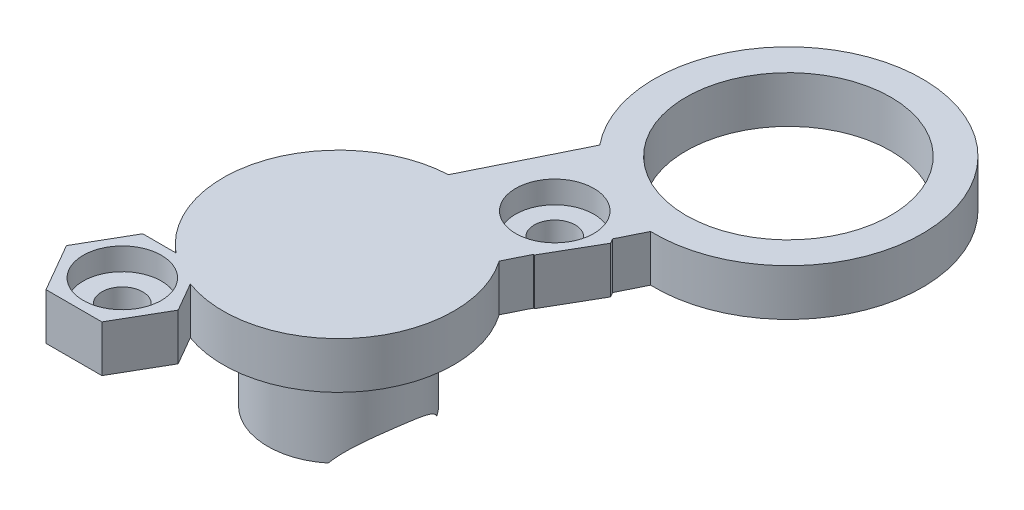
SolidWorks part; units mm, degrees
other "Compression Link 1 Moving Ball Retainer"
other "Compression Link 1 Moving Ball Retainer Left"
ref_plane "Front Plane" through (0, 0, 0) normal (0, 0, 1) x (1, 0, 0)
ref_plane "Top Plane" through (0, 0, 0) normal (0, 1, 0) x (1, 0, 0)
ref_plane "Right Plane" through (0, 0, 0) normal (1, 0, 0) x (0, 0, -1)
sketch3d "Retainer Feature 1 profile datum points"
  point P0 (-82.2724, -101, -15)
  point P1 (-72.2724, -101, -15)
  point P2 (-82.2724, -101, -5)
ref_plane "Retainer Feature 1 profile plane" through (0, -101, 0) normal (0, -1, 0) x (-1, 0, 0)
sketch "Retainer Feature 1 profile" plane through (0, -101, 0) normal (0, -1, 0) x (-1, 0, 0)
  circle A0 centre (82.2724, 15) radius 3.8
extrude "Retainer Feature 1" add sketch "Retainer Feature 1 profile" along normal blind 5.02 separate body
sketch3d "Retainer Feature 2 profile datum points"
  point P0 (-82.2724, -106, -15)
  point P1 (-72.2724, -106, -15)
  point P2 (-82.2724, -106, -5)
ref_plane "Retainer Feature 2 profile plane" through (0, -106, 0) normal (0, -1, 0) x (-1, 0, 0)
sketch "Retainer Feature 2 profile" plane through (0, -106, 0) normal (0, -1, 0) x (-1, 0, 0)
  circle A0 centre (82.2724, 15) radius 6.2
extrude "Retainer Feature 2" add sketch "Retainer Feature 2 profile" along normal blind 2.5
sketch3d "Middle Right Floating Compression Ball Retainer 1 Hexagonal Screw Pad 2 datum points"
  point P0 (-86.5224, -106, -7.6388)
  point P1 (-76.5224, -106, -7.6388)
  point P2 (-86.5224, -106, 2.3612)
ref_plane "Middle Right Floating Compression Ball Retainer 1 Hexagonal Screw Pad 2 plane" through (0, -106, 0) normal (0, -1, 0) x (-1, 0, 0)
sketch "Middle Right Floating Compression Ball Retainer 1 Hexagonal Screw Pad 2" plane through (0, -106, 0) normal (0, -1, 0) x (-1, 0, 0)
  line L0 (83.5224, 7.6388) -> (85.0224, 5.0407)
  line L1 (85.0224, 5.0407) -> (88.0224, 5.0407)
  line L2 (88.0224, 5.0407) -> (89.5224, 7.6388)
  line L3 (89.5224, 7.6388) -> (88.0224, 10.2369)
  line L4 (88.0224, 10.2369) -> (85.0224, 10.2369)
  line L5 (85.0224, 10.2369) -> (83.5224, 7.6388)
extrude "Retainer Feature 5" add sketch "Middle Right Floating Compression Ball Retainer 1 Hexagonal Screw Pad 2" along normal blind 2.5
sketch3d "Middle Right Floating Compression Ball Retainer 1 Hexagonal Screw Pad 5 datum points"
  point P0 (-78.0224, -106, -22.3612)
  point P1 (-68.0224, -106, -22.3612)
  point P2 (-78.0224, -106, -12.3612)
ref_plane "Middle Right Floating Compression Ball Retainer 1 Hexagonal Screw Pad 5 plane" through (0, -106, 0) normal (0, -1, 0) x (-1, 0, 0)
sketch "Middle Right Floating Compression Ball Retainer 1 Hexagonal Screw Pad 5" plane through (0, -106, 0) normal (0, -1, 0) x (-1, 0, 0)
  line L0 (75.0224, 22.3612) -> (76.5224, 19.7631)
  line L1 (76.5224, 19.7631) -> (79.5224, 19.7631)
  line L2 (79.5224, 19.7631) -> (81.0224, 22.3612)
  line L3 (81.0224, 22.3612) -> (79.5224, 24.9593)
  line L4 (79.5224, 24.9593) -> (76.5224, 24.9593)
  line L5 (76.5224, 24.9593) -> (75.0224, 22.3612)
extrude "Retainer Feature 8" add sketch "Middle Right Floating Compression Ball Retainer 1 Hexagonal Screw Pad 5" along normal blind 2.5
sketch3d "Retainer Feature 9 axis line"
  line L0 (-82.2724, -101, -25) -> (-82.2724, -101, -5) construction
ref_axis "Retainer Feature 9 axis" through (-82.2724, -101, -25) along (0, 0, 1)
sketch3d "Retainer Feature 9 profile datum points"
  point P0 (-82.2724, -101, -15)
  point P1 (-72.2724, -101, -15)
  point P2 (-82.2724, -101, -5)
ref_plane "Retainer Feature 9 profile plane" through (0, -101, 0) normal (0, -1, 0) x (-1, 0, 0)
sketch "Retainer Feature 9 profile" plane through (0, -101, 0) normal (0, -1, 0) x (-1, 0, 0)
  line L0 (82.2724, 11.85) -> (82.2724, 18.15)
  arc A0 (82.2724, 18.15) -> (82.2724, 11.85) centre (82.2724, 15) ccw
revolve "Retainer Feature 9" cut sketch "Retainer Feature 9 profile" angle 360 about axis through (-82.2724, -101, -25) along (0, 0, 1)
sketch3d "Middle Right Floating Compression Ball Retainer 1 Plate Sketch 49 datum points"
  point P0 (-82.2724, -106, -15)
  point P1 (-77.8481, -106, -23.968)
  point P2 (-73.3044, -106, -10.5757)
ref_plane "Middle Right Floating Compression Ball Retainer 1 Plate Sketch 49 plane" through (0, -106, 0) normal (0, -1, 0) x (-1, 0, 0)
sketch "Middle Right Floating Compression Ball Retainer 1 Plate Sketch 49" plane through (0, -106, 0) normal (0, -1, 0) x (-1, 0, 0)
  line L0 (84.9628, 16.3273) -> (76.9821, 32.5042)
  line L1 (76.9821, 32.5042) -> (71.6012, 29.8496)
  line L2 (71.6012, 29.8496) -> (79.582, 13.6727)
  line L3 (79.582, 13.6727) -> (84.9628, 16.3273)
extrude "Retainer Feature 12" add sketch "Middle Right Floating Compression Ball Retainer 1 Plate Sketch 49" along normal blind 2.5
sketch3d "Retainer Feature 13 profile datum points"
  point P0 (-74.2917, -106, -31.1769)
  point P1 (-64.2917, -106, -31.1769)
  point P2 (-74.2917, -106, -21.1769)
ref_plane "Retainer Feature 13 profile plane" through (0, -106, 0) normal (0, -1, 0) x (-1, 0, 0)
sketch "Retainer Feature 13 profile" plane through (0, -106, 0) normal (0, -1, 0) x (-1, 0, 0)
  circle A0 centre (74.2917, 31.1769) radius 7.2
extrude "Retainer Feature 13" add sketch "Retainer Feature 13 profile" along normal blind 2.5
sketch3d "Retainer Feature 14 profile datum points"
  point P0 (-74.2917, -105.9, -31.1769)
  point P1 (-64.2917, -105.9, -31.1769)
  point P2 (-74.2917, -105.9, -21.1769)
ref_plane "Retainer Feature 14 profile plane" through (0, -105.9, 0) normal (0, -1, 0) x (-1, 0, 0)
sketch "Retainer Feature 14 profile" plane through (0, -105.9, 0) normal (0, -1, 0) x (-1, 0, 0)
  circle A0 centre (74.2917, 31.1769) radius 5.5
extrude "Retainer Feature 14" cut sketch "Retainer Feature 14 profile" along normal blind 2.7
sketch3d "Retainer Feature 15 profile datum points"
  point P0 (-86.5224, -105, -7.6388)
  point P1 (-76.5224, -105, -7.6388)
  point P2 (-86.5224, -105, 2.3612)
ref_plane "Retainer Feature 15 profile plane" through (0, -105, 0) normal (0, -1, 0) x (-1, 0, 0)
sketch "Retainer Feature 15 profile" plane through (0, -105, 0) normal (0, -1, 0) x (-1, 0, 0)
  circle A0 centre (86.5224, 7.6388) radius 1.1
extrude "Retainer Feature 15" cut sketch "Retainer Feature 15 profile" along normal blind 3.75
sketch3d "Retainer Feature 16 profile datum points"
  point P0 (-86.5224, -107.3, -7.6388)
  point P1 (-76.5224, -107.3, -7.6388)
  point P2 (-86.5224, -107.3, 2.3612)
ref_plane "Retainer Feature 16 profile plane" through (0, -107.3, 0) normal (0, -1, 0) x (-1, 0, 0)
sketch "Retainer Feature 16 profile" plane through (0, -107.3, 0) normal (0, -1, 0) x (-1, 0, 0)
  circle A0 centre (86.5224, 7.6388) radius 2.1
extrude "Retainer Feature 16" cut sketch "Retainer Feature 16 profile" along normal blind 1.45
sketch3d "Retainer Feature 17 profile datum points"
  point P0 (-78.0224, -105, -22.3612)
  point P1 (-68.0224, -105, -22.3612)
  point P2 (-78.0224, -105, -12.3612)
ref_plane "Retainer Feature 17 profile plane" through (0, -105, 0) normal (0, -1, 0) x (-1, 0, 0)
sketch "Retainer Feature 17 profile" plane through (0, -105, 0) normal (0, -1, 0) x (-1, 0, 0)
  circle A0 centre (78.0224, 22.3612) radius 1.1
extrude "Retainer Feature 17" cut sketch "Retainer Feature 17 profile" along normal blind 3.75
sketch3d "Retainer Feature 18 profile datum points"
  point P0 (-78.0224, -107.3, -22.3612)
  point P1 (-68.0224, -107.3, -22.3612)
  point P2 (-78.0224, -107.3, -12.3612)
ref_plane "Retainer Feature 18 profile plane" through (0, -107.3, 0) normal (0, -1, 0) x (-1, 0, 0)
sketch "Retainer Feature 18 profile" plane through (0, -107.3, 0) normal (0, -1, 0) x (-1, 0, 0)
  circle A0 centre (78.0224, 22.3612) radius 2.1
extrude "Retainer Feature 18" cut sketch "Retainer Feature 18 profile" along normal blind 1.45
sketch3d "Articulation Throat axis line"
  line L0 (-90.6158, -106.3831, -16.1872) -> (-73.929, -95.6169, -13.8128) construction
ref_axis "Articulation Throat axis" through (-90.6158, -106.3831, -16.1872) along (0.8343, 0.5383, 0.1187)
sketch3d "Articulation Throat Sketch datum points"
  point P0 (-82.2724, -101, -15)
  point P1 (-82.2724, -98.8462, -24.7653)
  point P2 (-73.929, -95.6169, -13.8128)
ref_plane "Articulation Throat Sketch plane" through (21.8481, -32.2924, -7.1221) normal (0.5512, -0.8148, -0.1797) x (-0.8343, -0.5383, -0.1187)
sketch "Articulation Throat Sketch" plane through (21.8481, -32.2924, -7.1221) normal (0.5512, -0.8148, -0.1797) x (-0.8343, -0.5383, -0.1187)
  line L0 (124.7935, -7.105) -> (124.7935, -4.805)
  line L1 (124.7935, -4.805) -> (101.7935, 1.915)
  line L2 (101.7935, 1.915) -> (101.7935, -7.105)
  line L3 (101.7935, -7.105) -> (124.7935, -7.105)
revolve "Articulation Throat" cut sketch "Articulation Throat Sketch" angle 360 about axis through (-90.6158, -106.3831, -16.1872) along (0.8343, 0.5383, 0.1187)
sketch3d "Mirror1 profile datum points"
  point P0 (0, 0, 0)
  point P1 (10, 0, 0)
  point P2 (0, 0, 10)
ref_plane "Mirror1 profile plane" through (0, 0, 0) normal (0, -1, 0) x (-1, 0, 0)
mirror "Mirror1" about plane through (0, 0, 0) normal (0, -1, 0) of bodies 113
delete or keep bodies "Remove1" type delete bodies bodies 113
